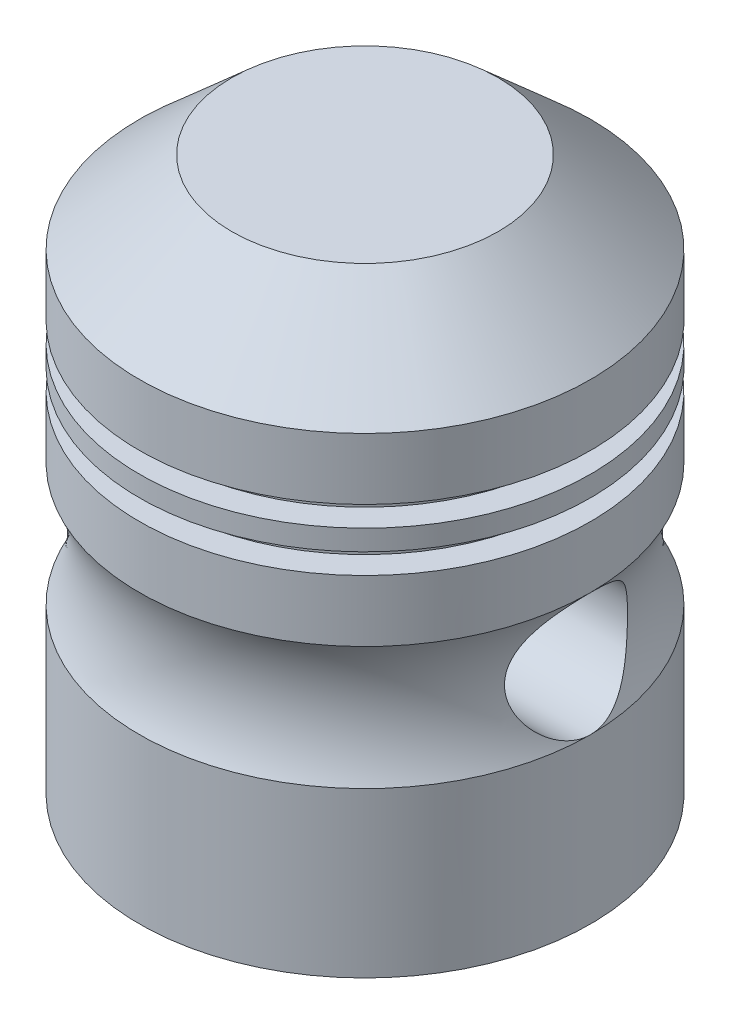
SolidWorks part; units mm, degrees
ref_plane "Front Plane" through (0, 0, 0) normal (0, 0, 1) x (1, 0, 0)
ref_plane "Top Plane" through (0, 0, 0) normal (0, 1, 0) x (1, 0, 0)
ref_plane "Right Plane" through (0, 0, 0) normal (1, 0, 0) x (0, 0, -1)
sketch "Sketch1" plane through (0, 0, 0) normal (0, 0, 1) x (1, 0, 0)
  line L0 (0, -30.9574) -> (0, 30.9574) construction
  line L1 (0, 27) -> (-6.5, 27)
  line L2 (-6.5, 27) -> (-11, 23)
  line L3 (-11, 23) -> (-11, 20)
  line L4 (-11, 20) -> (-9.75, 20)
  line L5 (-9.75, 20) -> (-9.75, 19)
  line L6 (-9.75, 19) -> (-11, 19)
  line L7 (-11, 19) -> (-11, 18)
  line L8 (-11, 18) -> (-9.75, 18)
  line L9 (-9.75, 18) -> (-9.75, 17)
  line L10 (-9.75, 17) -> (-11, 17)
  line L11 (-11, 17) -> (-11, 14)
  line L12 (-11, 0) -> (-11, 8)
  line L13 (-11, 0) -> (-9.75, 0)
  line L14 (-9.75, 0) -> (-9.75, 6)
  line L15 (-9.75, 6) -> (0, 6)
  line L16 (0, 6) -> (0, 27)
  arc A0 (-11, 14) -> (-11, 8) centre (-16.6307, 11) cw
  point P4 (0, 0)
  dimension "D12" = 6.38
  dimension "D1" = 27
  dimension "D2" = 13
  dimension "D3" = 23
  dimension "D4" = 20
  dimension "D5" = 19
  dimension "D6" = 18
  dimension "D7" = 17
  dimension "D8" = 19.5
  dimension "D9" = 11
  dimension "D10" = 14
  dimension "D11" = 8
  dimension "D13" = 6
revolve "Revolve1" add sketch "Sketch1" angle 360 about L0
sketch "Sketch2" plane through (0, 0, 0) normal (0, 1, 0) x (1, 0, 0)
  line L0 (0, -3.5) -> (0, 3.5) construction
  line L1 (-5, -3.5) -> (-5, 3.5)
  line L2 (5, -3.5) -> (5, 3.5)
  arc A0 (-5, -3.5) -> (5, -3.5) centre (0, -3.5) ccw
  arc A1 (5, 3.5) -> (-5, 3.5) centre (0, 3.5) ccw
  point P2 (0, 0)
  dimension "D1" = 7
  dimension "D2" = 10
extrude "Cut-Extrude1" cut sketch "Sketch2" along normal blind 19
sketch "Sketch3" plane through (0, 0, 0) normal (1, 0, 0) x (0, 0, -1)
  line L0 (-10.2507, 11) -> (10.2507, 11) construction
  circle A0 centre (0, 11) radius 3
  arc A1 (-11, 8) -> (-11, 14) centre (-16.6307, 11) ccw construction
  arc A2 (11, 14) -> (11, 8) centre (16.6307, 11) ccw construction
  point P10 (0, 0)
  dimension "D1" = 6
extrude "Cut-Extrude2" cut sketch "Sketch3" against normal through all both and the other way through all
